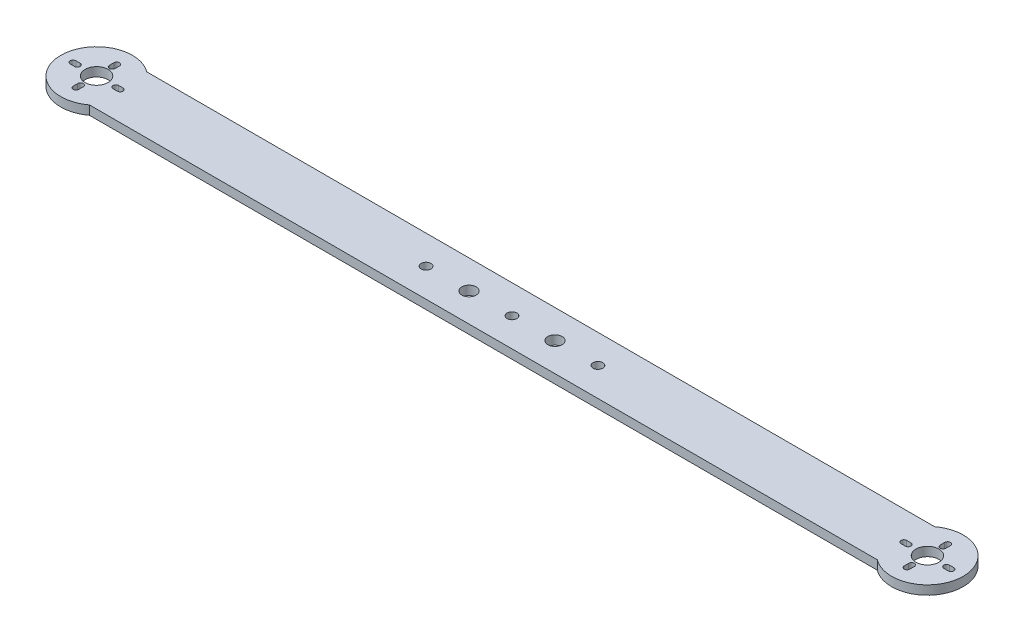
SolidWorks part; units mm, degrees
ref_plane "Front Plane" through (0, 0, 0) normal (0, 0, 1) x (1, 0, 0)
ref_plane "Top Plane" through (0, 0, 0) normal (0, 1, 0) x (1, 0, 0)
ref_plane "Right Plane" through (0, 0, 0) normal (1, 0, 0) x (0, 0, -1)
sketch "Sketch1" plane through (0, 0, 0) normal (0, 1, 0) x (1, 0, 0)
  line L0 (0, 12.7) -> (0, -12.7) construction
  line L1 (-174.625, 12.7) -> (174.625, 12.7)
  line L3 (-174.625, -12.7) -> (174.625, -12.7)
  arc A0 (-174.625, 12.7) -> (-174.625, -12.7) centre (-184.15, 0) ccw
  arc A1 (174.625, -12.7) -> (174.625, 12.7) centre (184.15, 0) ccw
  point P8 (0, 12.7)
  point P12 (0, 0)
  dimension "D3" = 31.75
  dimension "D4" = 31.75
extrude "Boss-Extrude1" add sketch "Sketch1" along normal blind 4
sketch "Sketch2" plane through (0, 4, 0) normal (0, 1, 0) x (1, 0, 0)
  line L0 (173.6914, 0) -> (175.6086, 0) construction
  line L1 (173.6914, 1.25) -> (175.6086, 1.25)
  line L2 (173.6914, -1.25) -> (175.6086, -1.25)
  line L3 (184.15, 0) -> (184.15, 3.2374) construction
  line L4 (194.6086, 0) -> (192.6914, 0) construction
  line L5 (194.6086, 1.25) -> (192.6914, 1.25)
  line L6 (194.6086, -1.25) -> (192.6914, -1.25)
  line L7 (184.15, 8.9209) -> (184.15, 6.921) construction
  line L8 (185.4, 8.9209) -> (185.4, 6.921)
  line L9 (182.9, 8.9209) -> (182.9, 6.921)
  line L10 (184.1914, -9.079) -> (184.1914, -7.079) construction
  line L11 (185.4414, -9.079) -> (185.4414, -7.079)
  line L12 (182.9414, -9.079) -> (182.9414, -7.079)
  line L13 (0, 0) -> (184.15, 0) construction
  line L14 (0, 0) -> (0, 12.7) construction
  line L15 (174.625, 12.7) -> (-174.625, 12.7) construction
  line L16 (-184.15, 0) -> (-184.15, 3.2374) construction
  line L17 (-184.1914, -9.079) -> (-184.1914, -7.079) construction
  line L18 (-185.4414, -9.079) -> (-185.4414, -7.079)
  line L19 (-182.9414, -9.079) -> (-182.9414, -7.079)
  line L20 (-184.15, 8.9209) -> (-184.15, 6.921) construction
  line L21 (-185.4, 8.9209) -> (-185.4, 6.921)
  line L22 (-182.9, 8.9209) -> (-182.9, 6.921)
  line L23 (-194.6086, 0) -> (-192.6914, 0) construction
  line L24 (-194.6086, 1.25) -> (-192.6914, 1.25)
  line L25 (-194.6086, -1.25) -> (-192.6914, -1.25)
  line L26 (-173.6914, 0) -> (-175.6086, 0) construction
  line L27 (-173.6914, 1.25) -> (-175.6086, 1.25)
  line L28 (-173.6914, -1.25) -> (-175.6086, -1.25)
  circle A0 centre (184.15, 0) radius 5.08
  arc A1 (173.6914, 1.25) -> (173.6914, -1.25) centre (173.6914, 0) ccw
  arc A2 (175.6086, -1.25) -> (175.6086, 1.25) centre (175.6086, 0) ccw
  arc A3 (194.6086, 1.25) -> (194.6086, -1.25) centre (194.6086, 0) cw
  arc A4 (192.6914, -1.25) -> (192.6914, 1.25) centre (192.6914, 0) cw
  arc A5 (185.4, 8.9209) -> (182.9, 8.9209) centre (184.15, 8.9209) ccw
  arc A6 (182.9, 6.921) -> (185.4, 6.921) centre (184.15, 6.921) ccw
  arc A7 (185.4414, -9.079) -> (182.9414, -9.079) centre (184.1914, -9.079) cw
  arc A8 (182.9414, -7.079) -> (185.4414, -7.079) centre (184.1914, -7.079) cw
  circle A9 centre (-184.15, 0) radius 5.08
  arc A10 (-185.4414, -9.079) -> (-182.9414, -9.079) centre (-184.1914, -9.079) ccw
  arc A11 (-182.9414, -7.079) -> (-185.4414, -7.079) centre (-184.1914, -7.079) ccw
  arc A12 (-185.4, 8.9209) -> (-182.9, 8.9209) centre (-184.15, 8.9209) cw
  arc A13 (-182.9, 6.921) -> (-185.4, 6.921) centre (-184.15, 6.921) cw
  arc A14 (-194.6086, 1.25) -> (-194.6086, -1.25) centre (-194.6086, 0) ccw
  arc A15 (-192.6914, -1.25) -> (-192.6914, 1.25) centre (-192.6914, 0) ccw
  arc A16 (-173.6914, 1.25) -> (-173.6914, -1.25) centre (-173.6914, 0) cw
  arc A17 (-175.6086, -1.25) -> (-175.6086, 1.25) centre (-175.6086, 0) cw
  point P4 (174.65, 0)
  point P12 (193.65, 0)
  point P19 (184.15, 7.921)
  point P26 (184.1914, -8.079)
  point P41 (-184.1914, -8.079)
  point P48 (-184.15, 7.921)
  point P55 (-193.65, 0)
  point P62 (-174.65, 0)
  dimension "D4" = 10.16
  dimension "D1" = 16
  dimension "D2" = 19
  dimension "D3" = 184.15
  dimension "D5" = 1.9999
extrude "Cut-Extrude1" cut sketch "Sketch2" against normal through all
sketch "Sketch3" plane through (0, 4, 0) normal (0, 1, 0) x (1, 0, 0)
  circle A0 centre (0, 0) radius 2.159
  circle A1 centre (38.1, 0) radius 2.159
  circle A2 centre (-38.1, 0) radius 2.159
  dimension "D1" = 38.1
  dimension "D3" = 4.318
  dimension "D4" = 4.318
  dimension "D5" = 4.318
  dimension "D2" = 38.1
extrude "Cut-Extrude2" cut sketch "Sketch3" against normal through all
sketch "Sketch4" plane through (0, 4, 0) normal (0, 1, 0) x (1, 0, 0)
  circle A0 centre (-19.05, 0) radius 3.175
  circle A1 centre (19.05, 0) radius 3.175
  dimension "D1" = 19.05
  dimension "D2" = 19.05
extrude "Cut-Extrude3" cut sketch "Sketch4" against normal through all
